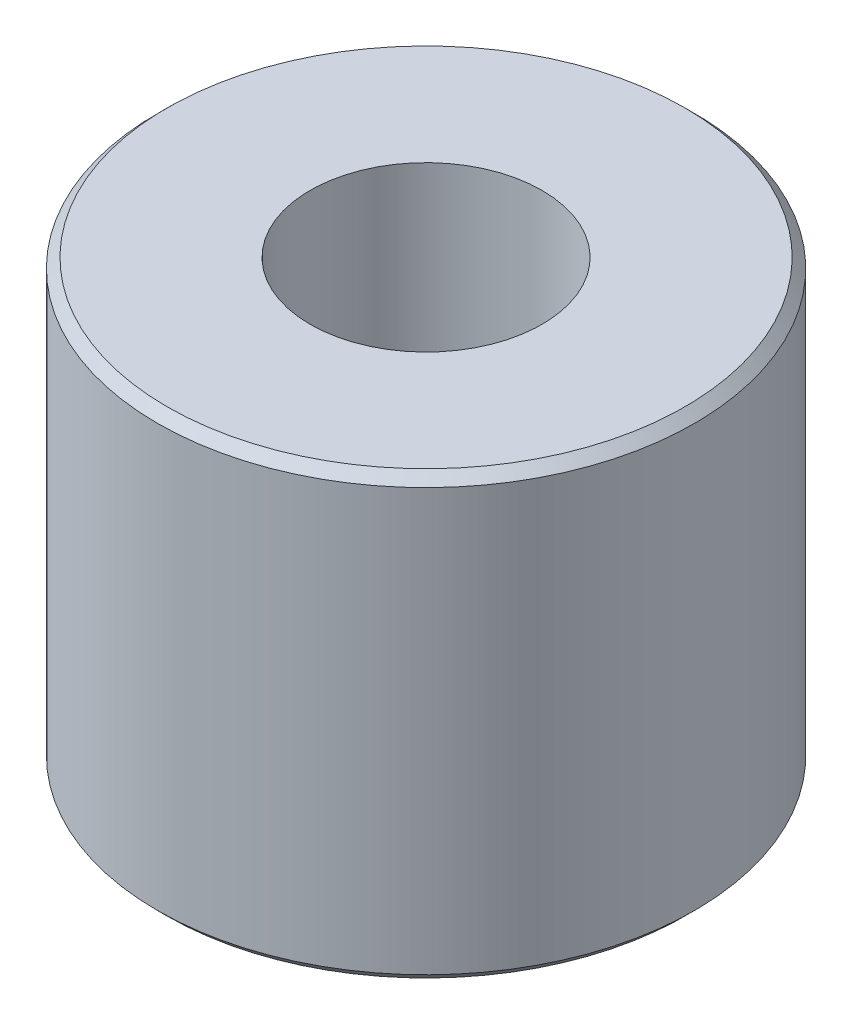
SolidWorks part; units mm, degrees
ref_plane "Front Plane" through (0, 0, 0) normal (0, 0, 1) x (1, 0, 0)
ref_plane "Top Plane" through (0, 0, 0) normal (0, 1, 0) x (1, 0, 0)
ref_plane "Right Plane" through (0, 0, 0) normal (1, 0, 0) x (0, 0, -1)
sketch "Sketch2" plane through (0, 0, 0) normal (0, 1, 0) x (1, 0, 0)
  circle A0 centre (0, 0) radius 14
  dimension "D1" = 28
extrude "Boss-Extrude1" add sketch "Sketch2" along normal blind 23
sketch "Sketch3" plane through (0, 23, 0) normal (0, 1, 0) x (1, 0, 0)
  circle A0 centre (0, 0) radius 6.05
  dimension "D1" = 12.1
extrude "Cut-Extrude1" cut sketch "Sketch3" against normal through all
chamfer "Chamfer1" distance 0.5 angle 45 2 edges at (0, 0, 14) (0, 23, 14)
